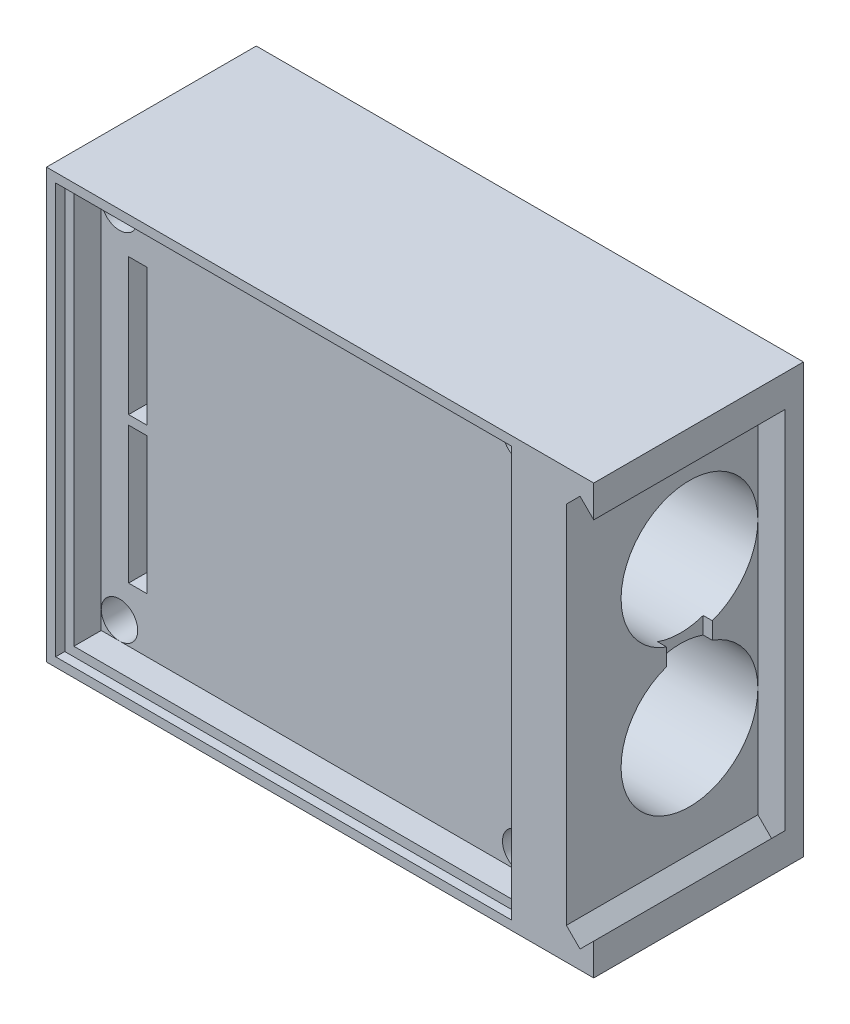
SolidWorks part; units mm, degrees
ref_plane "Plan de face" through (0, 0, 0) normal (0, 0, 1) x (1, 0, 0)
ref_plane "Plan de dessus" through (0, 0, 0) normal (0, 1, 0) x (1, 0, 0)
ref_plane "Plan de droite" through (0, 0, 0) normal (1, 0, 0) x (0, 0, -1)
sketch "Esquisse1" plane through (0, 0, 0) normal (0, 0, 1) x (1, 0, 0)
  line L1 (0, 0) -> (60, 0)
  line L2 (0, 0) -> (0, 47)
  line L3 (0, 47) -> (60, 47)
  line L4 (60, 0) -> (60, 47)
  dimension "D1" = 47
  dimension "D2" = 60
extrude "Boss.-Extru.1" add sketch "Esquisse1" along normal blind 23
sketch "Esquisse2" plane through (0, 0, 23) normal (0, 0, 1) x (1, 0, 0)
  line L0 (60, 47) -> (0, 47) construction
  line L1 (1, 46) -> (51, 46)
  line L2 (1, 46) -> (1, 1)
  line L3 (1, 1) -> (51, 1)
  line L4 (51, 46) -> (51, 1)
  line L5 (0, 47) -> (0, 0) construction
  dimension "D1" = 50
  dimension "D2" = 45
  dimension "D3" = 1
  dimension "D4" = 1
extrude "Enlèv. mat.-Extru.1" cut sketch "Esquisse2" against normal blind 1
sketch "Esquisse3" plane through (0, 0, 22) normal (0, 0, 1) x (1, 0, 0)
  line L0 (1, 46) -> (1, 1) construction
  line L1 (2, 45) -> (50, 45)
  line L2 (2, 45) -> (2, 2)
  line L3 (2, 2) -> (50, 2)
  line L4 (50, 45) -> (50, 2)
  line L5 (51, 46) -> (1, 46) construction
  dimension "D1" = 48
  dimension "D2" = 43
  dimension "D3" = 1
  dimension "D4" = 1
extrude "Enlèv. mat.-Extru.2" cut sketch "Esquisse3" against normal blind 3
sketch "Esquisse4" plane through (0, 0, 23) normal (0, 0, 1) x (1, 0, 0)
  line L0 (60, 43.5) -> (58.5, 45)
  line L1 (60, 0) -> (60, 47) construction
  line L2 (58.5, 45) -> (57, 43.5)
  line L3 (57, 43.5) -> (57, 3.5)
  line L4 (57, 3.5) -> (58.5, 2)
  line L5 (58.5, 2) -> (60, 3.5)
  line L6 (60, 3.5) -> (60, 43.5)
  line L8 (0, 0) -> (60, 0) construction
  line L9 (60, 47) -> (0, 47) construction
  dimension "D1" = 3
  dimension "D2" = 2
  dimension "D3" = 90
  dimension "D4" = 90
  dimension "D5" = 2
  dimension "D6" = 135
  dimension "D7" = 135
  dimension "D8" = 0
  dimension "D9" = 0
extrude "Enlèv. mat.-Extru.3" cut sketch "Esquisse4" against normal blind 21
sketch "Esquisse5" plane through (57, 0, 0) normal (1, 0, 0) x (0, 0, -1)
  line L0 (0, 0) -> (0, 47) construction
  line L1 (-23, 0) -> (0, 0) construction
  circle A0 centre (-9.5, 31.5) radius 7.5
  circle A1 centre (-9.5, 15.5) radius 7.5
  dimension "D3" = 15
  dimension "D4" = 15
  dimension "D1" = 9.5
  dimension "D2" = 9.5
  dimension "D5" = 16
  dimension "D6" = 15.5
extrude "Enlèv. mat.-Extru.4" cut sketch "Esquisse5" against normal blind 51
sketch "Esquisse8" plane through (0, 0, 19) normal (0, 0, 1) x (1, 0, 0)
  line L0 (57, 43.5) -> (57, 3.5) construction
  line L1 (5, 39) -> (7, 39)
  line L2 (5, 39) -> (5, 24)
  line L3 (5, 24) -> (7, 24)
  line L4 (7, 39) -> (7, 24)
  line L5 (5, 23) -> (7, 23)
  line L6 (5, 23) -> (5, 8)
  line L7 (5, 8) -> (7, 8)
  line L8 (7, 23) -> (7, 8)
  line L9 (60, 47) -> (0, 47) construction
  dimension "D1" = 2
  dimension "D2" = 2
  dimension "D3" = 50
  dimension "D4" = 50
  dimension "D5" = 15
  dimension "D6" = 15
  dimension "D7" = 1
  dimension "D8" = 8
extrude "Enlèv. mat.-Extru.5" cut sketch "Esquisse8" against normal blind 17
sketch "Esquisse9" plane through (0, 0, 0) normal (0, 0, -1) x (-1, 0, 0)
  line L0 (0, 47) -> (0, 0) construction
  line L1 (0, 0) -> (-60, 0) construction
  line L2 (-60, 47) -> (0, 47) construction
  line L3 (-51, 1) -> (-51, 46) construction
  circle A0 centre (-48, 43) radius 2
  circle A1 centre (-4, 43) radius 2
  circle A2 centre (-4, 4) radius 2
  circle A3 centre (-48, 4) radius 2
  dimension "D1" = 4
  dimension "D2" = 4
  dimension "D3" = 4
  dimension "D4" = 4
  dimension "D5" = 4
  dimension "D6" = 4
  dimension "D7" = 4
  dimension "D8" = 4
  dimension "D9" = 4
  dimension "D10" = 4
  dimension "D11" = 3
  dimension "D12" = 3
extrude "Enlèv. mat.-Extru.6" cut sketch "Esquisse9" against normal through all
chamfer "Chanfrein1" distance 1 angle 55 4 edges at (46, 4, 0) (46, 43, 0) (2, 4, 0) (2, 43, 0)
sketch "Esquisse10" plane through (57, 0, 0) normal (1, 0, 0) x (0, 0, -1)
  line L0 (-2, 31.5) -> (-2, 15.5) construction
  line L1 (-12, 27.683) -> (-7, 27.683)
  line L2 (-12, 27.683) -> (-12, 17.683)
  line L3 (-12, 17.683) -> (-7, 17.683)
  line L4 (-7, 27.683) -> (-7, 17.683)
  dimension "D1" = 10
  dimension "D2" = 5
  dimension "D3" = 5
extrude "Enlèv. mat.-Extru.7" cut sketch "Esquisse10" against normal blind 1
